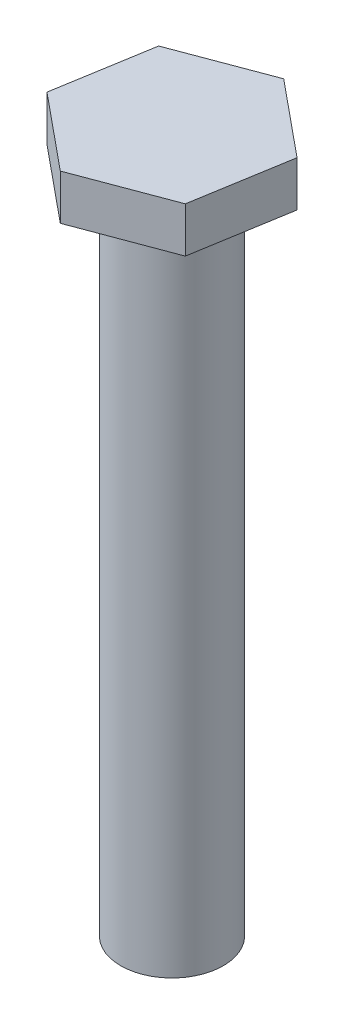
SolidWorks part; units mm, degrees
material "AISI 316 Stainless Steel Sheet (SS)"
ref_plane "Front Plane" through (0, 0, 0) normal (0, 0, 1) x (1, 0, 0)
ref_plane "Top Plane" through (0, 0, 0) normal (0, 1, 0) x (1, 0, 0)
ref_plane "Right Plane" through (0, 0, 0) normal (1, 0, 0) x (0, 0, -1)
sketch "Sketch1" plane through (0, 0, 0) normal (0, 1, 0) x (1, 0, 0)
  circle A0 centre (0, 0) radius 7.9375
  dimension "D1" = 15.875
extrude "Shaft" add sketch "Sketch1" against normal blind 101.6
sketch "Sketch2" plane through (0, 0, 0) normal (0, 1, 0) x (1, 0, 0)
  line L1 (11.595, -9.5335) -> (14.0538, 5.2748)
  line L2 (14.0538, 5.2748) -> (2.4588, 14.8084)
  line L3 (2.4588, 14.8084) -> (-11.595, 9.5335)
  line L4 (-11.595, 9.5335) -> (-14.0538, -5.2748)
  line L5 (-14.0538, -5.2748) -> (-2.4588, -14.8084)
  line L6 (-2.4588, -14.8084) -> (11.595, -9.5335)
  circle A0 centre (0, 0) radius 13 construction
  dimension "D1" = 13
extrude "Head" add sketch "Sketch2" along normal blind 7
equation "\"boltLength\"= 4in"
equation "\"boltDiameter\"= 5in / 8"
equation "\"D1@Sketch1\"=\"boltDiameter\""
equation "\"D1@Shaft\" = \"boltLength\""
